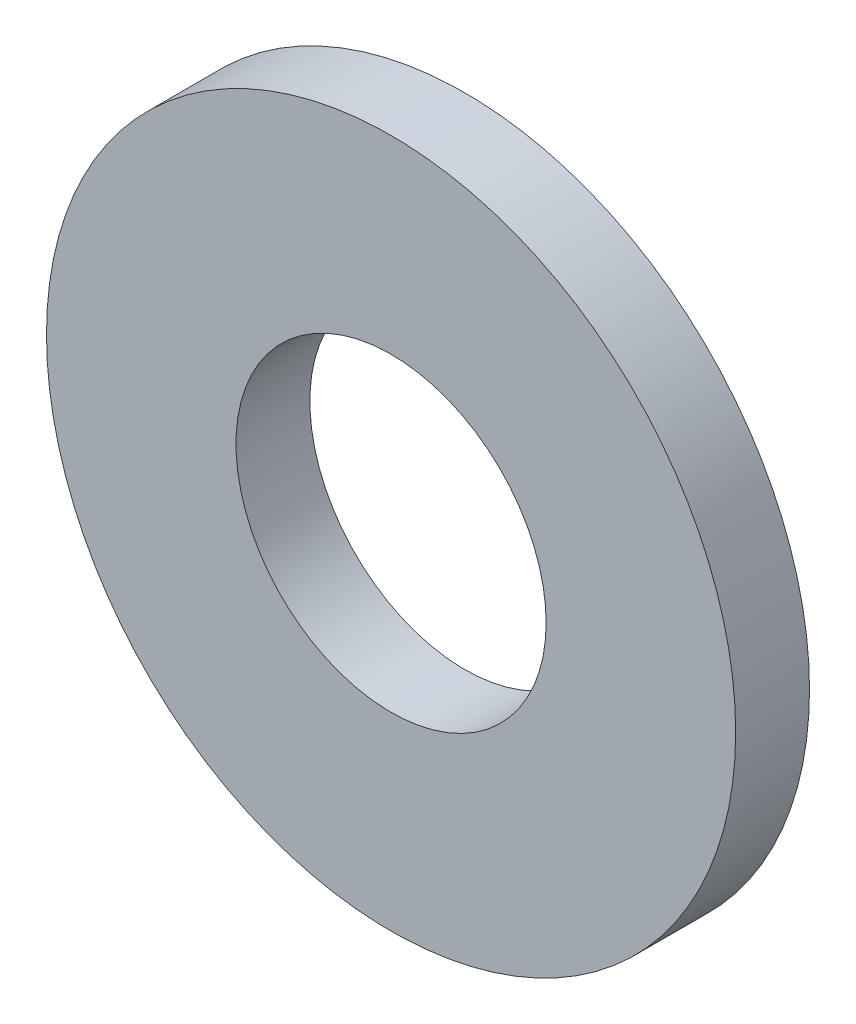
SolidWorks part; units mm, degrees
material "Полиэфирная смола"
ref_plane "Спереди" through (0, 0, 0) normal (0, 0, 1) x (1, 0, 0)
ref_plane "Сверху" through (0, 0, 0) normal (0, 1, 0) x (1, 0, 0)
ref_plane "Справа" through (0, 0, 0) normal (1, 0, 0) x (0, 0, -1)
sketch "Эскиз1" plane through (0, 0, 0) normal (0, 0, 1) x (1, 0, 0)
  circle A0 centre (0, 0) radius 7
  circle A1 centre (0, 0) radius 3.15
  dimension "D1" = 6.3
  dimension "D2" = 14
extrude "Бобышка-Вытянуть1" add sketch "Эскиз1" along normal blind 1.5
